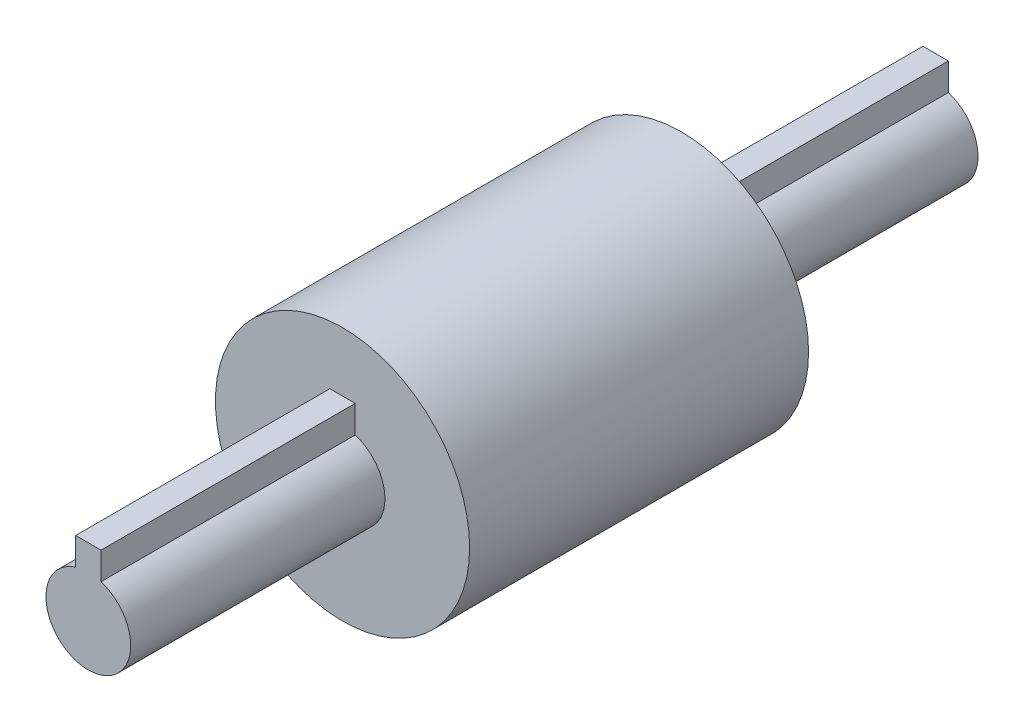
SolidWorks part; units mm, degrees
ref_plane "前视基准面" through (0, 0, 0) normal (0, 0, 1) x (1, 0, 0)
ref_plane "上视基准面" through (0, 0, 0) normal (0, 1, 0) x (1, 0, 0)
ref_plane "右视基准面" through (0, 0, 0) normal (1, 0, 0) x (0, 0, -1)
other "Configuration Table"
sketch "草图1" plane through (0, 0, 0) normal (0, 0, 1) x (1, 0, 0)
  line L0 (0, 0) -> (-1.5, 0)
  line L1 (-1.5, 0) -> (-1.5, 8)
  line L2 (-1.5, 8) -> (1.5, 8)
  line L3 (1.5, 8) -> (1.5, 0)
  line L4 (1.5, 0) -> (0, 0)
  circle A0 centre (0, 0) radius 5
extrude "凸台-拉伸1" add sketch "草图1" along normal blind 30 contours A0 L3 L2 L1 | L3 A0 L1 L0 L4 | L1 A0 L3 L4 L0
sketch "草图2" plane through (0, 0, 30) normal (0, 0, 1) x (1, 0, 0)
  circle A0 centre (0, 0) radius 15
extrude "凸台-拉伸2" add sketch "草图2" along normal blind 25
sketch "草图3" plane through (0, 0, 55) normal (0, 0, 1) x (1, 0, 0)
  line L0 (0, 0) -> (-1.5, 0)
  line L1 (-1.5, 0) -> (-1.5, 8)
  line L2 (-1.5, 8) -> (1.5, 8)
  line L3 (0, 0) -> (1.5, 0)
  line L4 (1.5, 0) -> (1.5, 8)
  circle A0 centre (0, 0) radius 5
extrude "凸台-拉伸3" add sketch "草图3" along normal blind 30 contours L1 A0 L4 L3 L0 | A0 L4 L2 L1 | L4 A0 L1 L0 L3
sketch "草图4" plane through (0, 0, 55) normal (0, 0, 1) x (1, 0, 0)
  circle A0 centre (0, 0) radius 15
extrude "凸台-拉伸4" add sketch "草图4" along normal blind 15
sketch "草图5" plane through (0, 0, 85) normal (0, 0, 1) x (1, 0, 0)
  line L0 (-1.5, 8) -> (-1.5, 4.7697)
  line L1 (-1.5, 8) -> (1.5, 8)
  line L2 (1.5, 8) -> (1.5, 4.7697)
  circle A0 centre (0, 0) radius 5
  arc M1 (-1.5, 4.7697) -> (1.5, 4.7697) centre (0, 0) ccw
  line M2 (1.5, 4.7697) -> (1.5, 8)
  line M3 (1.5, 8) -> (-1.5, 8)
  line M4 (-1.5, 8) -> (-1.5, 4.7697)
extrude "凸台-拉伸5" add sketch "草图5" along normal blind 15 contours A0 M1 | A0 M2 M3 M4
